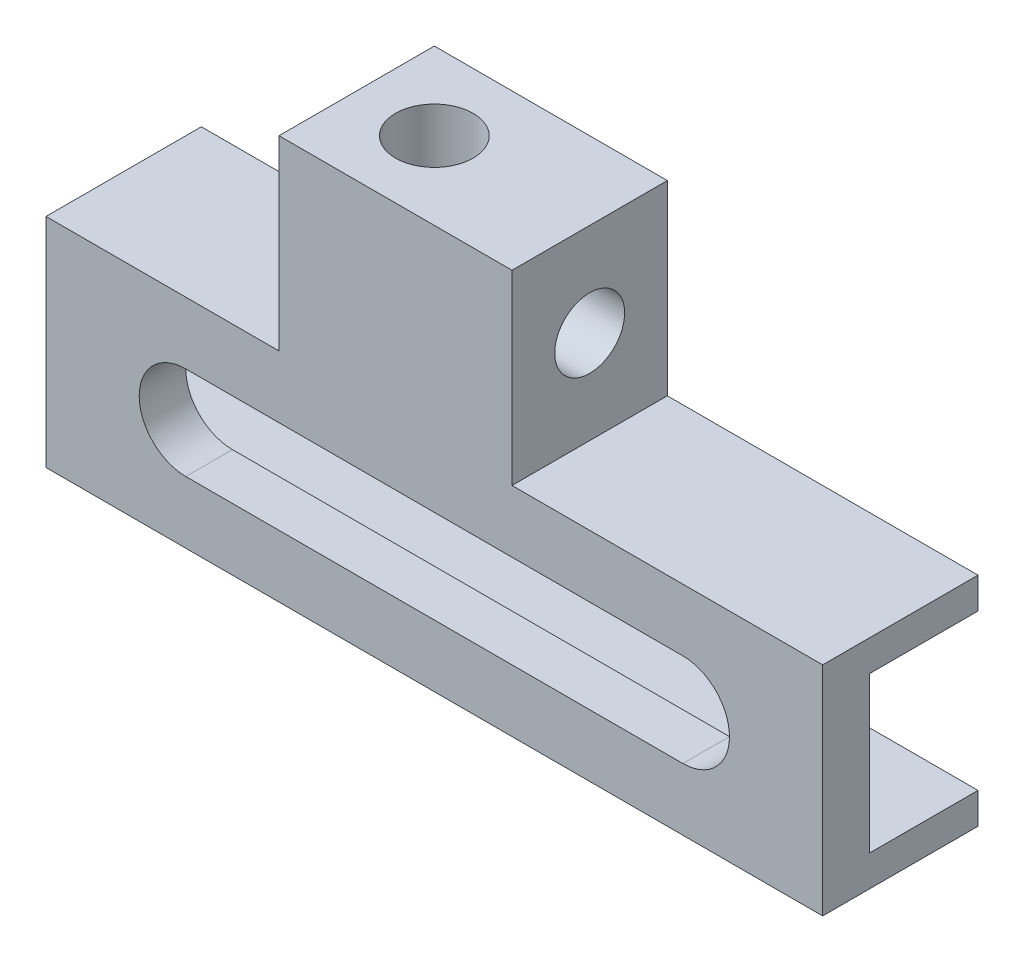
SolidWorks part; units mm, degrees
ref_plane "Front Plane" through (0, 0, 0) normal (0, 0, 1) x (1, 0, 0)
ref_plane "Top Plane" through (0, 0, 0) normal (0, 1, 0) x (1, 0, 0)
ref_plane "Right Plane" through (0, 0, 0) normal (1, 0, 0) x (0, 0, -1)
sketch "Sketch2" plane through (0, 0, 0) normal (1, 0, 0) x (0, 0, -1)
  line L0 (0, -7) -> (0, 7)
  line L1 (0, 7) -> (10, 7)
  line L2 (10, 7) -> (10, 5)
  line L3 (10, 5) -> (3, 5)
  line L4 (3, 5) -> (3, -5)
  line L5 (3, 0) -> (0, 0) construction
  line L6 (10, -5) -> (3, -5)
  line L7 (10, -7) -> (10, -5)
  line L8 (0, -7) -> (10, -7)
  dimension "D1" = 7
  dimension "D2" = 10
  dimension "D3" = 5
  dimension "D4" = 3
extrude "Boss-Extrude1" add sketch "Sketch2" along normal blind 50
sketch "Sketch3" plane through (0, 0, -3) normal (0, 0, -1) x (-1, 0, 0)
  line L0 (-41, 0) -> (-9, 0) construction
  line L1 (-41, 3) -> (-9, 3)
  line L2 (-41, -3) -> (-9, -3)
  line L3 (-50, -5) -> (-50, 5) construction
  arc A0 (-41, 3) -> (-41, -3) centre (-41, 0) ccw
  arc A1 (-9, -3) -> (-9, 3) centre (-9, 0) ccw
  point P2 (-25, 0)
  dimension "D1" = 3
  dimension "D2" = 9
  dimension "D3" = 9
extrude "Cut-Extrude1" cut sketch "Sketch3" against normal through all
sketch "Sketch4" plane through (0, 7, 0) normal (0, 1, 0) x (1, 0, 0)
  line L0 (50, 10) -> (0, 10) construction
  line L1 (15, 10) -> (30, 10)
  line L2 (15, 10) -> (15, 0)
  line L3 (15, 0) -> (30, 0)
  line L4 (30, 10) -> (30, 0)
  line L5 (50, 0) -> (0, 0) construction
  line L6 (0, 10) -> (0, 0) construction
  dimension "D1" = 15
  dimension "D2" = 15
extrude "Boss-Extrude2" add sketch "Sketch4" along normal blind 12
sketch "Sketch5" plane through (0, 19, 0) normal (0, 1, 0) x (1, 0, 0)
  line L0 (30, 0) -> (30, 10) construction
  circle A0 centre (20, 5) radius 2.5
  dimension "D1" = 5
  dimension "D2" = 10
extrude "Cut-Extrude2" cut sketch "Sketch5" against normal blind 10
sketch "Sketch6" plane through (30, 0, 0) normal (1, 0, 0) x (0, 0, -1)
  line L0 (10, 7) -> (0, 19) construction
  circle A0 centre (5, 13) radius 2.25
  dimension "D1" = 4.5
extrude "Cut-Extrude3" cut sketch "Sketch6" against normal up to surface (8.9103 mm away)
ref_plane "Plane1" through (0, 0, -5) normal (0, 0, 1) x (1, 0, 0)
